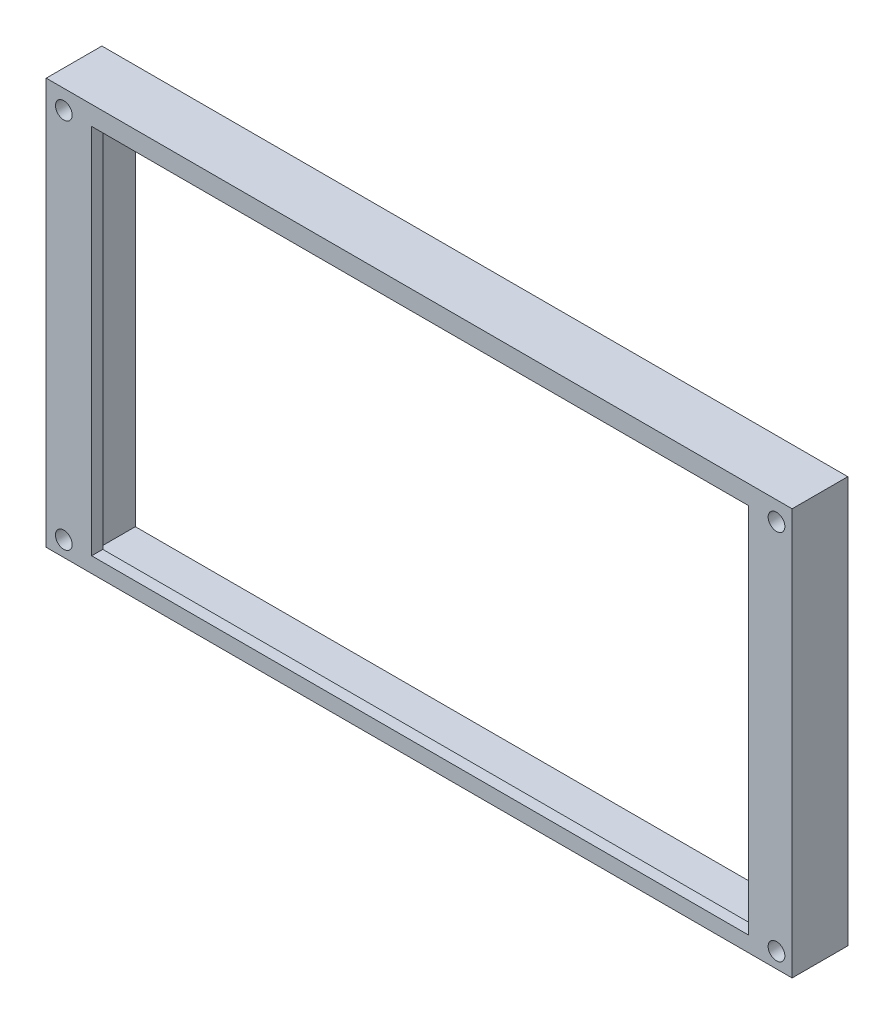
SolidWorks part; units mm, degrees
ref_plane "前视基准面" through (0, 0, 0) normal (0, 0, 1) x (1, 0, 0)
ref_plane "上视基准面" through (0, 0, 0) normal (0, 1, 0) x (1, 0, 0)
ref_plane "右视基准面" through (0, 0, 0) normal (1, 0, 0) x (0, 0, -1)
other "Configuration Table"
sketch "草图1" plane through (0, 0, 0) normal (0, 0, 1) x (1, 0, 0)
  line L1 (-40.7225, 42.7994) -> (85.2775, 42.7994)
  line L2 (-40.7225, 42.7994) -> (-40.7225, -30.2006)
  line L3 (-40.7225, -30.2006) -> (85.2775, -30.2006)
  line L4 (85.2775, 42.7994) -> (85.2775, -30.2006)
  line L5 (85.2775, 42.7994) -> (81.9661, 41.0219)
  line L7 (-38.7063, 41.0219) -> (83.2937, 41.0219)
  line L8 (-38.7063, 41.0219) -> (-38.7063, -28.9781)
  line L9 (-38.7063, -28.9781) -> (83.2937, -28.9781)
  line L10 (83.2937, 41.0219) -> (83.2937, -28.9781)
  point P4 (17.2775, 6.2994)
  dimension "D1" = 73
  dimension "D2" = 126
  dimension "D3" = 70
  dimension "D4" = 122
extrude "凸台-拉伸1" add sketch "草图1" against normal blind 8
sketch "草图5" plane through (0, 0, 0) normal (0, 0, 1) x (1, 0, 0)
  line L1 (-40.7225, 42.7994) -> (85.2775, 42.7994)
  line L2 (-40.7225, 42.7994) -> (-40.7225, -30.2006)
  line L3 (-40.7225, -30.2006) -> (85.2775, -30.2006)
  line L4 (85.2775, 42.7994) -> (85.2775, -30.2006)
  line L5 (-36.5585, 39.3731) -> (81.4706, 39.3731)
  line L6 (-36.5585, 39.3731) -> (-36.5585, -27.4327)
  line L7 (-36.5585, -27.4327) -> (81.4706, -27.4327)
  line L8 (81.4706, 39.3731) -> (81.4706, -27.4327)
  dimension "D1" = 73
  dimension "D2" = 126
  dimension "D3" = 66.8058
  dimension "D4" = 118.0291
extrude "凸台-拉伸2" add sketch "草图5" along normal blind 2
sketch "草图7" plane through (0, 0, -8) normal (0, 0, -1) x (-1, 0, 0)
  line L5 (-85.2775, 42.7994) -> (-89.2775, 42.7994)
  line L6 (-85.2775, 42.7994) -> (-85.2775, -30.2006)
  line L7 (-85.2775, -30.2006) -> (-89.2775, -30.2006)
  line L8 (-89.2775, 42.7994) -> (-89.2775, -30.2006)
  dimension "D1" = 73
  dimension "D2" = 4
extrude "凸台-拉伸3" add sketch "草图7" against normal blind 2
sketch "草图8" plane through (0, 0, -8) normal (0, 0, -1) x (-1, 0, 0)
  line L1 (40.7225, 42.7994) -> (44.7225, 42.7994)
  line L2 (40.7225, 42.7994) -> (40.7225, -30.2006)
  line L3 (40.7225, -30.2006) -> (44.7225, -30.2006)
  line L4 (44.7225, 42.7994) -> (44.7225, -30.2006)
  dimension "D1" = 73
  dimension "D2" = 4
extrude "凸台-拉伸5" add sketch "草图8" against normal blind 2
sketch "草图10" plane through (0, 0, -6) normal (0, 0, 1) x (1, 0, 0)
  line L1 (85.2775, 42.7994) -> (89.2775, 42.7994)
  line L2 (85.2775, 42.7994) -> (85.2775, -30.2006)
  line L3 (85.2775, -30.2006) -> (89.2775, -30.2006)
  line L4 (89.2775, 42.7994) -> (89.2775, -30.2006)
  line L5 (-44.7225, 42.7994) -> (-40.7225, 42.7994)
  line L6 (-44.7225, 42.7994) -> (-44.7225, -30.2006)
  line L7 (-44.7225, -30.2006) -> (-40.7225, -30.2006)
  line L8 (-40.7225, 42.7994) -> (-40.7225, -30.2006)
  dimension "D1" = 73
  dimension "D2" = 4
  dimension "D3" = 73
  dimension "D4" = 4
extrude "凸台-拉伸6" add sketch "草图10" along normal blind 5
sketch "草图12" plane through (0, 0, -1) normal (0, 0, 1) x (1, 0, 0)
  line L1 (-44.7225, 42.7994) -> (-40.7225, 42.7994)
  line L2 (-44.7225, 42.7994) -> (-44.7225, -30.2006)
  line L3 (-44.7225, -30.2006) -> (-40.7225, -30.2006)
  line L4 (-40.7225, 42.7994) -> (-40.7225, -30.2006)
  line L5 (89.2775, 42.7994) -> (85.2775, 42.7994)
  line L6 (89.2775, 42.7994) -> (89.2775, -30.2006)
  line L7 (89.2775, -30.2006) -> (85.2775, -30.2006)
  line L8 (85.2775, 42.7994) -> (85.2775, -30.2006)
  dimension "D1" = 73
  dimension "D2" = 4
  dimension "D3" = 73
  dimension "D4" = 4
extrude "凸台-拉伸7" add sketch "草图12" along normal blind 3
sketch "草图13" plane through (0, 0, 2) normal (0, 0, 1) x (1, 0, 0)
  line L0 (-36.5585, 39.3731) -> (-36.5585, -27.4327) construction
  line L5 (-41.5585, 39.3731) -> (86.4706, 39.3731)
  line L6 (-41.5585, 39.3731) -> (-41.5585, -27.4327)
  line L7 (-41.5585, -27.4327) -> (86.4706, -27.4327)
  line L8 (86.4706, 39.3731) -> (86.4706, -27.4327)
  line L9 (81.4706, -27.4327) -> (81.4706, 39.3731) construction
  circle A1 centre (-41.5585, 39.3731) radius 1.5
  circle A2 centre (-41.5585, -27.4327) radius 1.5
  circle A3 centre (86.4706, -27.4327) radius 1.5
  circle A4 centre (86.4706, 39.3731) radius 1.5
  dimension "D1" = 66.8058
  dimension "D3" = 5
  dimension "D4" = 5
extrude "切除-拉伸1" cut sketch "草图13" against normal through all contours L7 A3 L8 | L8 A3 L7 | L6 A2 L7 | L7 A2 L6 | L5 A1 L6 | L6 A1 L5 | L8 A4 L5 | L5 A4 L8
